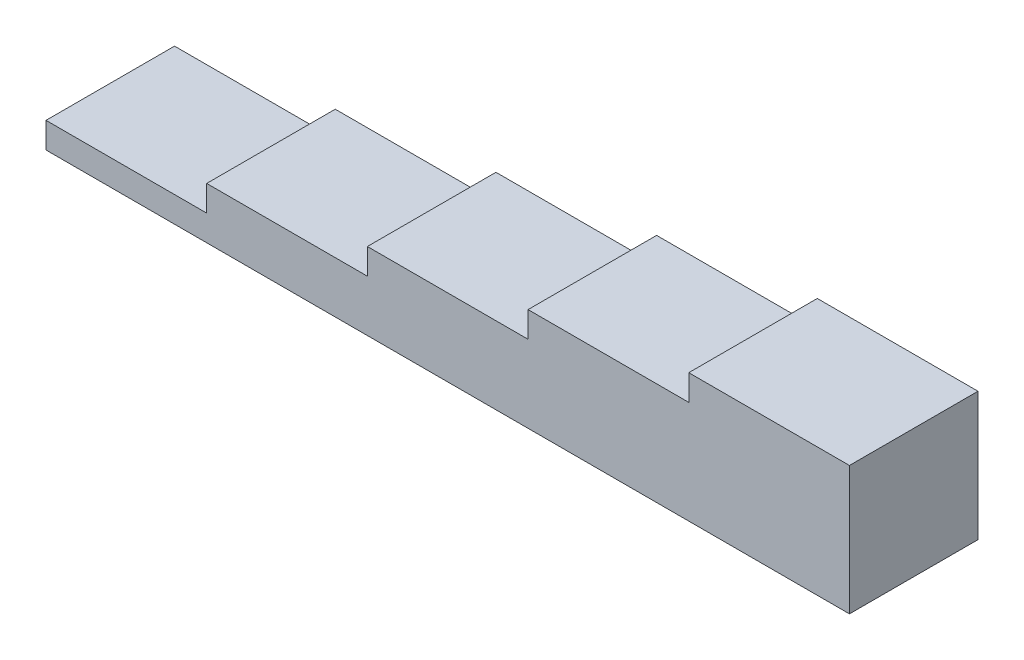
SolidWorks part; units mm, degrees
ref_plane "前视基准面" through (0, 0, 0) normal (0, 0, 1) x (1, 0, 0)
ref_plane "上视基准面" through (0, 0, 0) normal (0, 1, 0) x (1, 0, 0)
ref_plane "右视基准面" through (0, 0, 0) normal (1, 0, 0) x (0, 0, -1)
sketch "草图1" plane through (0, 0, 0) normal (0, 0, 1) x (1, 0, 0)
  line L0 (0, 0) -> (0, 40)
  line L1 (0, 40) -> (250, 40)
  line L2 (250, 40) -> (250, 80)
  line L3 (250, 80) -> (500, 80)
  line L4 (500, 80) -> (500, 120)
  line L5 (500, 120) -> (750, 120)
  line L6 (750, 120) -> (750, 160)
  line L7 (750, 160) -> (1000, 160)
  line L8 (1000, 160) -> (1000, 200)
  line L9 (1000, 200) -> (1250, 200)
  line L10 (1250, 200) -> (1250, 0)
  line L11 (1250, 0) -> (0, 0)
extrude "凸台-拉伸1" add sketch "草图1" along normal blind 200 contours L11 L0 L1 L2 L3 L4 L5 L6 L7 L8 L9 L10
